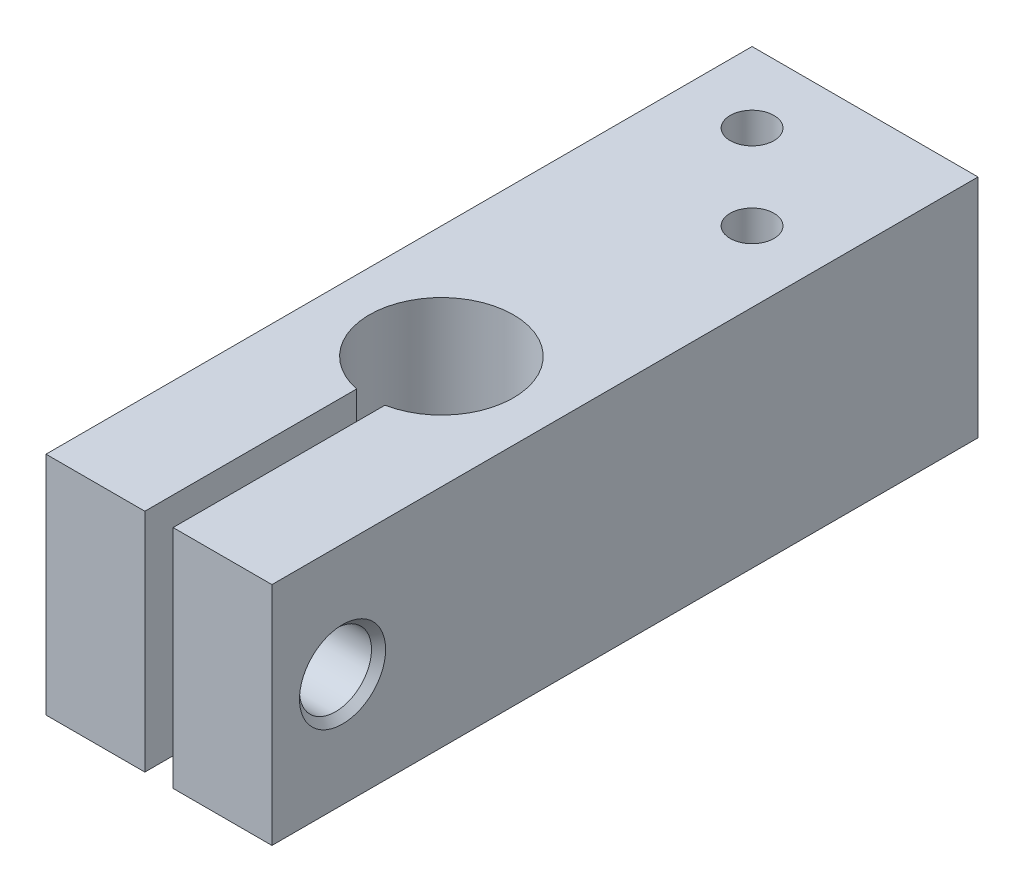
SolidWorks part; units mm, degrees
material "6063-T6"
ref_plane "Front Plane" through (0, 0, 0) normal (0, 0, 1) x (1, 0, 0)
ref_plane "Top Plane" through (0, 0, 0) normal (0, 1, 0) x (1, 0, 0)
ref_plane "Right Plane" through (0, 0, 0) normal (1, 0, 0) x (0, 0, -1)
sketch "Sketch1" plane through (0, 0, 0) normal (0, 0, 1) x (1, 0, 0)
  line L1 (8, -8) -> (-8, -8)
  line L2 (8, -8) -> (8, 8)
  line L3 (8, 8) -> (-8, 8)
  line L4 (-8, -8) -> (-8, 8)
  line L5 (8, -8) -> (-8, 8) construction
  line L6 (8, 8) -> (-8, -8) construction
  point P0 (0, 0)
  dimension "D1" = 16
  dimension "D2" = 16
extrude "Base" add sketch "Sketch1" along normal blind 50
sketch "Sketch2" plane through (0, 8, 0) normal (0, 1, 0) x (1, 0, 0)
  line L0 (-1, -50) -> (-1, -34)
  line L1 (8, -50) -> (-8, -50) construction
  line L2 (1, -50) -> (1, -34)
  line L3 (0, 0) -> (0, -9.2456) construction
  line L4 (-1, -34) -> (1, -34)
  dimension "D1" = 16
  dimension "D3" = 2
extrude "RodSlot" cut sketch "Sketch2" against normal through all
hole_wizard "Ø5.1 (5.1) free hole for screw" positions "Sketch7" profile "Sketch8" hole size "Ø5.1" standard "ANSI Metric"
sketch "Sketch7" plane through (8, 0, 0) normal (1, 0, 0) x (0, 0, -1)
  line L0 (-50, -8) -> (-50, 8) construction
  point P0 (-45, 0)
  dimension "D1" = 5
sketch "Sketch8" plane through (8, 0, 45) normal (0, 1, 0) x (0, 0, -1)
  line L0 (0, 0) -> (0, 8.5562)
  line L1 (0, 8.5562) -> (2.55, 7.5)
  line L2 (2.55, 7.5) -> (2.55, 0.5)
  line L3 (2.55, 0.5) -> (3.05, 0)
  line L5 (3.05, 0) -> (0, 0)
  line L6 (-2.55, 0.5) -> (-3.05, 0) construction
  line L10 (0, 8.5562) -> (-2.55, 7.5) construction
  line L11 (0, -6.35) -> (0, 107.95) construction
  dimension "Hole Dia." = 5.1
  dimension "Hole Depth" = 7.5
  dimension "Near C'Sink Dia." = 6.1
  dimension "Near C'Sink Angle" = 90
  dimension "Drill Angle" = 135
hole_wizard "M5x0.8 Tapped Hole for rod screw" positions "Sketch4" profile "Sketch5" tap size "M5x0.8" standard "ANSI Metric"
sketch "Sketch4" plane through (-8, 0, 0) normal (-1, 0, 0) x (0, 0, 1)
  point P0 (45, 0)
  point P3 (0, 0)
  point P6 (45, 0)
cosmetic thread "Hole Thread1" parameters "D1"=7, "D2"=5
sketch "Sketch5" plane through (-8, 0, 45) normal (0, 1, 0) x (0, 0, 1)
  line L0 (0, 0) -> (0, 8.9)
  line L1 (0, 8.9) -> (2.1, 7.6382)
  line L2 (2.1, 7.6382) -> (2.1, 0)
  line L5 (2.1, 0) -> (0, 0)
  line L10 (0, 8.9) -> (-2.1, 7.6382) construction
  line L11 (0, -6.35) -> (0, 107.95) construction
  dimension "Tap Drill Dia." = 4.2
  dimension "Tap Drill Depth" = 8.9
  dimension "Drill Angle" = 118
hole_wizard "Ø3.1 (3.1) screw holes" positions "Sketch9" profile "Sketch10" hole size "Ø3.1" standard "ANSI Metric" end condition through all
sketch "Sketch9" plane through (0, -8, 0) normal (0, -1, 0) x (-1, 0, 0)
  line L0 (8, 0) -> (-8, 0) construction
  line L1 (-8, -50) -> (-8, 0) construction
  point P0 (3, -5)
  point P2 (-3, -11)
  dimension "D1" = 11
  dimension "D2" = 5
  dimension "D3" = 11
  dimension "D4" = 5
sketch "Sketch10" plane through (-3, -8, 5) normal (1, 0, 0) x (0, 0, -1)
  line L0 (0, 0) -> (0, 16)
  line L1 (0, 16) -> (1.55, 16)
  line L2 (1.55, 16) -> (1.55, 0)
  line L5 (1.55, 0) -> (0, 0)
  line L11 (0, -6.35) -> (0, 107.95) construction
  dimension "Thru Hole Dia." = 3.1
  dimension "Thru Hole Depth" = 16
hole_wizard "Ø10.2 (10.2) Rod Hole" positions "Sketch11" profile "Sketch12" hole size "Ø10.2" standard "ANSI Metric" end condition through all
sketch "Sketch11" plane through (0, 8, 0) normal (0, 1, 0) x (1, 0, 0)
  line L1 (8, -50) -> (1, -50) construction
  point P0 (0, -30)
  point P5 (0, 0)
  point P6 (0, 0)
  dimension "D1" = 20
sketch "Sketch12" plane through (0, 8, 30) normal (1, 0, 0) x (0, 0, 1)
  line L0 (0, 0) -> (0, 16)
  line L1 (0, 16) -> (5.1, 16)
  line L2 (5.1, 16) -> (5.1, 0)
  line L5 (5.1, 0) -> (0, 0)
  line L11 (0, -6.35) -> (0, 107.95) construction
  dimension "Thru Hole Dia." = 10.2
  dimension "Thru Hole Depth" = 16
equation "\"D2@Sketch1\"=\"D1@Sketch1\""
